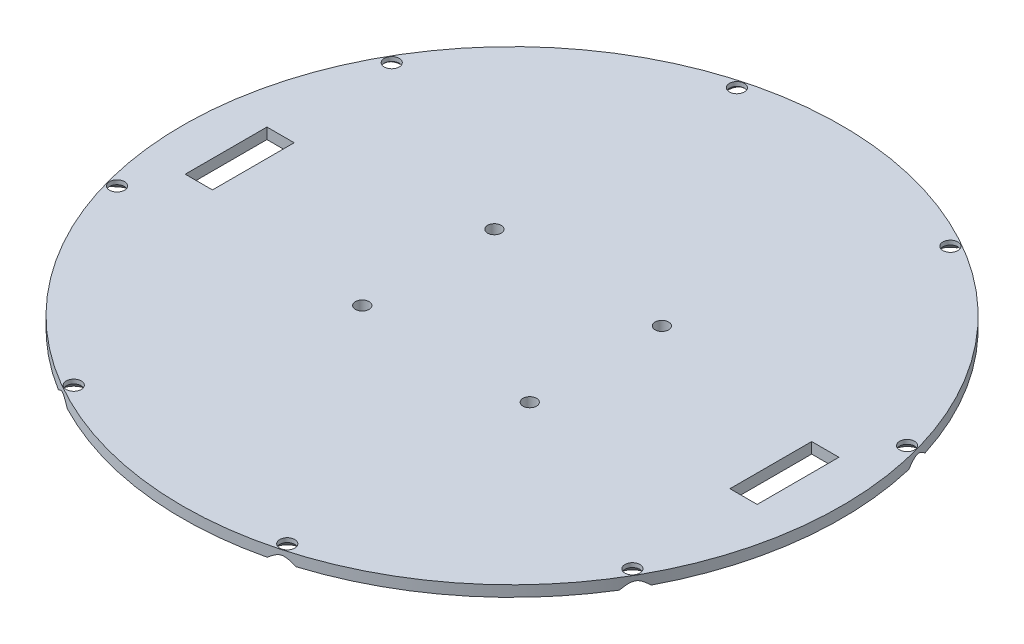
SolidWorks part; units mm, degrees
ref_plane "Front Plane" through (0, 0, 0) normal (0, 0, 1) x (1, 0, 0)
ref_plane "Top Plane" through (0, 0, 0) normal (0, 1, 0) x (1, 0, 0)
ref_plane "Right Plane" through (0, 0, 0) normal (1, 0, 0) x (0, 0, -1)
sketch "Bottom" plane through (0, 0, 0) normal (0, 1, 0) x (-1, 0, 0)
  line L0 (0, 0) -> (100, 0) construction
  line L1 (0, 2.4909) -> (0, -2.4909) construction
  line L2 (105, -15) -> (95, -15)
  line L3 (105, -15) -> (105, 15)
  line L4 (105, 15) -> (95, 15)
  line L5 (95, -15) -> (95, 15)
  line L6 (105, -15) -> (95, 15) construction
  line L7 (105, 15) -> (95, -15) construction
  line L8 (-105, 15) -> (-95, 15)
  line L9 (-95, -15) -> (-95, 15)
  line L10 (-105, -15) -> (-95, -15)
  line L11 (-105, -15) -> (-105, 15)
  line L12 (-105, 15) -> (-95, -15) construction
  line L13 (-105, -15) -> (-95, 15) construction
  circle A0 centre (0, 0) radius 121
  circle A1 centre (-30.75, -24.25) radius 2.5 construction
  circle A2 centre (30.75, -24.25) radius 2.5 construction
  circle A3 centre (30.75, 24.25) radius 2.5 construction
  circle A4 centre (-30.75, 24.25) radius 2.5 construction
  circle A5 centre (-30.75, -24.25) radius 2.5
  circle A6 centre (30.75, -24.25) radius 2.5
  circle A7 centre (30.75, 24.25) radius 2.5
  circle A8 centre (-30.75, 24.25) radius 2.5
  point P8 (0, 0)
  dimension "D1" = 242
  dimension "D2" = 100
  dimension "D3" = 30
  dimension "D4" = 10
extrude "Bottom-Extrude" add sketch "Bottom" along normal blind 4
hole_wizard "" positions "Sketch1" profile "Sketch2" countersink size "M5" standard "ISO"
sketch "Sketch1" plane through (-40.1386, 0, -6.2357) normal (0, -1, 0) x (0.8691, 0, 0.4946)
  circle A0 centre (37.9687, -14.4349) radius 118
  point P28 (-80.0313, -14.4349)
  point P38 (-45.4699, 69.0037)
  point P39 (37.9687, 103.5651)
  point P40 (121.4073, 69.0037)
  point P41 (155.9687, -14.4349)
  point P42 (121.4073, -97.8735)
  point P43 (37.9687, -132.4349)
  point P44 (-45.4699, -97.8735)
sketch "Sketch2" plane through (-31.2435, 0, -113.7886) normal (1, 0, 0) x (0, 0, -1)
  line L0 (0, 0) -> (0, 21.6524)
  line L1 (0, 21.6524) -> (2.75, 20)
  line L2 (2.75, 20) -> (2.75, 2.45)
  line L3 (2.75, 2.45) -> (5.2, 0)
  line L4 (5.2, 0) -> (0, 0)
  line L5 (-2.75, 2.45) -> (-5.2, 0) construction
  line L6 (0, 21.6524) -> (-2.75, 20) construction
  line L7 (0, -6.35) -> (0, 107.95) construction
  dimension "Hole Dia." = 5.5
  dimension "Hole Depth" = 20
  dimension "Near C'Sink Dia." = 10.4
  dimension "Near C'Sink Angle" = 90
  dimension "Drill Angle" = 118
hole_wizard "CSK for M5 Countersunk Raised Head Screw1" [suppressed] positions "Sketch3" profile "Sketch4" countersink size "M5" standard "ISO"
sketch "Sketch3" plane through (-38.4851, 0, 12.9956) normal (0, -1, 0) x (0.9993, 0, 0.0376)
  point P91 (6.3277, -37.5103)
  point P95 (69.6097, 8.6405)
  point P98 (67.7842, -39.8252)
  point P101 (8.1533, 10.9553)
sketch "Sketch4" plane through (-30.75, 0, -24.25) normal (1, 0, 0) x (0, 0, -1)
  line L0 (0, 0) -> (0, 21.6524)
  line L1 (0, 21.6524) -> (2.75, 20)
  line L2 (2.75, 20) -> (2.75, 2.45)
  line L3 (2.75, 2.45) -> (5.2, 0)
  line L4 (5.2, 0) -> (0, 0)
  line L5 (-2.75, 2.45) -> (-5.2, 0) construction
  line L6 (0, 21.6524) -> (-2.75, 20) construction
  line L7 (0, -6.35) -> (0, 107.95) construction
  dimension "Hole Dia." = 5.5
  dimension "Hole Depth" = 20
  dimension "Near C'Sink Dia." = 10.4
  dimension "Near C'Sink Angle" = 90
  dimension "Drill Angle" = 118
sketch "Sketch5" plane through (0, 4, 0) normal (0, -1, 0) x (1, 0, 0)
  line L0 (0, 0) -> (0, 75) construction
  line L1 (0, -2.4909) -> (0, 2.4909) construction
  circle A0 centre (0, 75) radius 6.7868
  dimension "D1" = 75
sketch "Sketch6" plane through (0, 0, 0) normal (0, 1, 0) x (1, 0, 0)
  line L0 (-95, -21.37) -> (-95, 21.37) construction
  line L1 (-95, 85.8074) -> (-137.3625, 85.8074)
  line L2 (-95, 85.8074) -> (-95, -93.576)
  line L3 (-95, -93.576) -> (-137.3625, -93.576)
  line L4 (-137.3625, 85.8074) -> (-137.3625, -93.576)
  line L5 (-95, -15) -> (-95, 15) construction
  line L7 (0, -2.4909) -> (0, 2.4909) construction
  line L8 (137.3625, 85.8074) -> (137.3625, -93.576)
  line L9 (95, -93.576) -> (137.3625, -93.576)
  line L10 (95, 85.8074) -> (95, -93.576)
  line L11 (95, 85.8074) -> (137.3625, 85.8074)
  point P7 (-95, 0)
  point P19 (95, 0)
  dimension "D4" = 0
  dimension "D5" = 0
extrude "Cut-Extrude1" [suppressed] cut sketch "Sketch6" along normal through all
equation "\"D1@Bottom\"=\"outer radius\""
equation "\"D2@Bottom\"=\"wheel distance\""
equation "\"D1@Bottom-Extrude\"=\"top bottom thickness\""
equation "\"inner radius\"= 230"
equation "\"wall thickness\"= 6\t"
equation "\"outer radius\"= \"inner radius\" + 2 * \"wall thickness\""
equation "\"height\" = 40"
equation "\"wheel distance\" = 100"
equation "\"screw length\" = 15"
equation "\"top bottom thickness\" = 4"
equation "\"accel distance\" = 75"
equation "\"tolerance\" = 0.3"
equation "\"wheel hole width\" = 30"
equation "\"D1@Sketch5\"=\"accel distance\""
